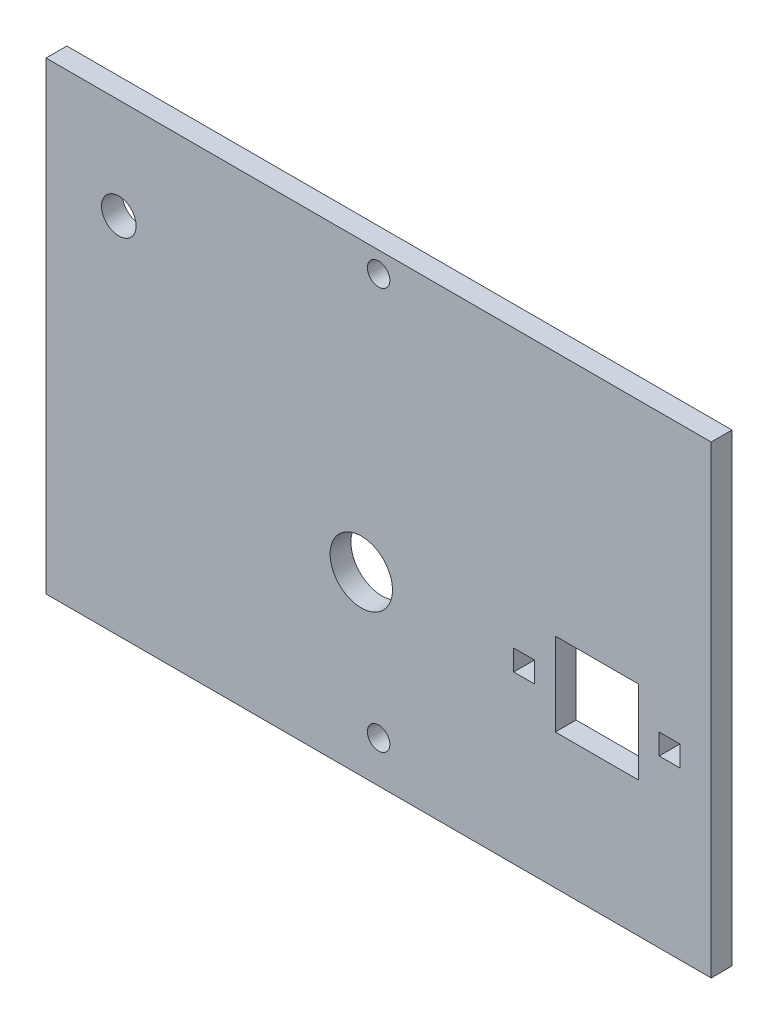
SolidWorks part; units mm, degrees
ref_plane "Alzado" through (0, 0, 0) normal (0, 0, 1) x (1, 0, 0)
ref_plane "Planta" through (0, 0, 0) normal (0, 1, 0) x (1, 0, 0)
ref_plane "Vista lateral" through (0, 0, 0) normal (1, 0, 0) x (0, 0, -1)
sketch "Croquis1" plane through (0, 0, 0) normal (0, 0, 1) x (1, 0, 0)
  line L1 (-48, -33.5) -> (48, -33.5)
  line L2 (-48, -33.5) -> (-48, 33.5)
  line L3 (-48, 33.5) -> (48, 33.5)
  line L4 (48, -33.5) -> (48, 33.5)
  line L5 (-48, -33.5) -> (48, 33.5) construction
  line L6 (-48, 33.5) -> (48, -33.5) construction
  point P0 (0, 0)
  dimension "D1" = 96
  dimension "D2" = 67
extrude "Saliente-Extruir1" add sketch "Croquis1" along normal blind 3
sketch "Croquis2" plane through (0, 0, 0) normal (0, 0, 1) x (1, 0, 0)
  line L0 (48, 33.5) -> (-48, 33.5) construction
  line L1 (-48, 33.5) -> (-48, -33.5) construction
  line L2 (-48, -33.5) -> (48, -33.5) construction
  line L3 (48, -33.5) -> (48, 33.5) construction
  line L4 (25.5, -2) -> (37.5, -2)
  line L5 (25.5, -2) -> (25.5, -14)
  line L6 (25.5, -14) -> (37.5, -14)
  line L7 (37.5, -2) -> (37.5, -14)
  line L8 (25.5, -2) -> (37.5, -14) construction
  line L9 (25.5, -14) -> (37.5, -2) construction
  line L11 (19.5, -9.5) -> (22.5, -9.5)
  line L12 (19.5, -9.5) -> (19.5, -6.5)
  line L13 (19.5, -6.5) -> (22.5, -6.5)
  line L14 (22.5, -9.5) -> (22.5, -6.5)
  line L15 (19.5, -9.5) -> (22.5, -6.5) construction
  line L16 (19.5, -6.5) -> (22.5, -9.5) construction
  line L17 (40.5, -9.5) -> (43.5, -9.5)
  line L18 (40.5, -9.5) -> (40.5, -6.5)
  line L19 (40.5, -6.5) -> (43.5, -6.5)
  line L20 (43.5, -9.5) -> (43.5, -6.5)
  line L21 (40.5, -9.5) -> (43.5, -6.5) construction
  line L22 (40.5, -6.5) -> (43.5, -9.5) construction
  circle A0 centre (-37.5, 19) radius 2.5
  circle A1 centre (-2.5, -8) radius 4.5
  circle A2 centre (0, 30.5) radius 1.625 construction
  circle A3 centre (0, -27.5) radius 1.625 construction
  circle A4 centre (0, 30.5) radius 1.625
  circle A5 centre (0, -27.5) radius 1.625
  point P10 (31.5, -8)
  point P23 (21, -8)
  point P28 (42, -8)
  point P33 (0, 0)
  point P34 (0, 0)
  point P35 (16.7224, -11.2353)
  point P36 (0, 0)
  point P37 (15.4432, -6.5)
  dimension "D1" = 5
  dimension "D2" = 14.5
  dimension "D3" = 10.5
  dimension "D4" = 9
  dimension "D5" = 25.5
  dimension "D6" = 45.5
  dimension "D7" = 12
  dimension "D8" = 10.5
  dimension "D9" = 3
  dimension "D10" = 3
  dimension "D11" = 3
extrude "Cortar-Extruir1" cut sketch "Croquis2" along normal through all
sketch "Sketch3" plane through (0, 0, 3) normal (0, 0, 1) x (1, 0, 0)
  line L0 (-5.5534, 7.4138) -> (-7.3809, 8.9287)
  line L1 (-7.3809, 8.9287) -> (-8.4496, 8.9293)
  line L2 (-8.4594, 13.0301) -> (-7.3709, 13.0385)
  line L3 (-7.3709, 13.0385) -> (-5.4893, 14.597)
  line L4 (-12.2452, -0.2207) -> (-11.9045, 0.2103)
  line L5 (-11.9045, 0.2103) -> (-10.5652, -1.129)
  line L6 (-10.5652, -1.129) -> (-9.226, -2.4682)
  line L7 (-9.226, -2.4682) -> (-9.5723, -2.9498)
  line L8 (-11.1649, -7.1254) -> (-11.1929, -7.3082)
  line L9 (-11.1929, -7.3082) -> (-13.0965, -7.3082)
  line L10 (-13.0965, -7.3082) -> (-15, -7.3082)
  line L11 (-15, -7.3082) -> (-14.9678, -6.9791)
  line L12 (-9.5247, -0.0724) -> (-10.8537, 1.2572)
  line L13 (-10.8537, 1.2572) -> (-10.6676, 1.4249)
  line L14 (-3.5202, 4.4696) -> (-3.2398, 4.5)
  line L15 (-3.2398, 4.5) -> (-3.2398, 2.5703)
  line L16 (-3.2398, 2.5703) -> (-3.2398, 0.6405)
  line L17 (-3.2398, 0.6405) -> (-3.3982, 0.6404)
  line L18 (-12.2452, -0.2207) -> (-11.9045, 0.2103)
  line L19 (-11.9045, 0.2103) -> (-10.5652, -1.129)
  line L20 (-10.5652, -1.129) -> (-9.226, -2.4682)
  line L21 (-9.226, -2.4682) -> (-9.5723, -2.9498)
  line L22 (-11.1649, -7.1254) -> (-11.1929, -7.3082)
  line L23 (-11.1929, -7.3082) -> (-13.0965, -7.3082)
  line L24 (-13.0965, -7.3082) -> (-15, -7.3082)
  line L25 (-15, -7.3082) -> (-14.9678, -6.9791)
  line L26 (-9.5247, -0.0724) -> (-10.8537, 1.2572)
  line L27 (-10.8537, 1.2572) -> (-10.6676, 1.4249)
  line L28 (-3.5202, 4.4696) -> (-3.2398, 4.5)
  line L29 (-3.2398, 4.5) -> (-3.2398, 2.5703)
  line L30 (-3.2398, 2.5703) -> (-3.2398, 0.6405)
  line L31 (-3.2398, 0.6405) -> (-3.3982, 0.6404)
  line L32 (7.2452, -0.2246) -> (6.9045, 0.2064)
  line L33 (6.9045, 0.2064) -> (5.5653, -1.1328)
  line L34 (5.5653, -1.1328) -> (4.226, -2.4721)
  line L35 (4.226, -2.4721) -> (4.5723, -2.9536)
  line L36 (6.1649, -7.1292) -> (6.1929, -7.3121)
  line L37 (6.1929, -7.3121) -> (8.0965, -7.3121)
  line L38 (8.0965, -7.3121) -> (10, -7.3121)
  line L39 (10, -7.3121) -> (9.9678, -6.9829)
  line L40 (4.5247, -0.0763) -> (5.8537, 1.2534)
  line L41 (5.8537, 1.2534) -> (5.6676, 1.421)
  line L42 (-1.4798, 4.4657) -> (-1.7602, 4.4962)
  line L43 (-1.7602, 4.4962) -> (-1.7602, 2.5664)
  line L44 (-1.7602, 2.5664) -> (-1.7602, 0.6367)
  line L45 (-1.7602, 0.6367) -> (-1.6017, 0.6366)
  spline S6 degree 3 poles (2.1798, 5.1128) (2.0212, 5.1868) (1.8251, 5.3837) (1.7541, 5.5401) knots 0 0 0 0 1 1 1 1
  spline S7 degree 3 poles (1.7541, 5.5401) (1.6866, 5.6887) (1.6805, 5.9358) (1.7407, 6.0799) knots 0 0 0 0 1 1 1 1
  spline S8 degree 3 poles (1.7407, 6.0799) (1.7647, 6.1374) (1.8882, 6.3198) (2.0151, 6.4853) knots 0 0 0 0 1 1 1 1
  spline S9 degree 3 poles (2.0151, 6.4853) (2.8091, 7.5204) (3.2972, 8.6684) (3.4875, 9.9482) knots 0 0 0 0 1 1 1 1
  spline S10 degree 3 poles (3.4875, 9.9482) (3.5521, 10.3829) (3.5739, 11.2404) (3.5311, 11.6623) knots 0 0 0 0 1 1 1 1
  spline S11 degree 3 poles (3.5311, 11.6623) (3.3809, 13.1412) (2.8186, 14.5037) (1.8919, 15.6347) knots 0 0 0 0 1 1 1 1
  spline S12 degree 3 poles (1.8919, 15.6347) (1.5927, 15.9997) (1.5659, 16.0534) (1.5661, 16.2873) knots 0 0 0 0 1 1 1 1
  spline S13 degree 3 poles (1.5661, 16.2873) (1.5662, 16.5274) (1.6362, 16.6705) (1.8456, 16.8588) knots 0 0 0 0 1 1 1 1
  spline S14 degree 3 poles (1.8456, 16.8588) (2.085, 17.074) (2.3614, 17.1164) (2.6354, 16.9798) knots 0 0 0 0 1 1 1 1
  spline S15 degree 3 poles (2.6354, 16.9798) (2.7982, 16.8988) (3.059, 16.6076) (3.4139, 16.1109) knots 0 0 0 0 1 1 1 1
  spline S16 degree 3 poles (3.4139, 16.1109) (5.55, 13.1214) (5.6127, 9.1441) (3.572, 6.0768) knots 0 0 0 0 1 1 1 1
  spline S17 degree 3 poles (3.572, 6.0768) (3.2805, 5.6386) (2.98, 5.2704) (2.8261, 5.1626) knots 0 0 0 0 1 1 1 1
  spline S18 degree 3 poles (2.8261, 5.1626) (2.6598, 5.0462) (2.3702, 5.0239) (2.1798, 5.1128) knots 0 0 0 0 1 1 1 1
  spline S19 degree 3 poles (-3.3936, 5.6887) (-3.5414, 5.7438) (-3.4712, 5.6877) (-5.5534, 7.4138) knots 0 0 0 0 1 1 1 1
  spline S20 degree 3 poles (-8.4496, 8.9293) (-9.4614, 8.9299) (-9.5254, 8.9332) (-9.6513, 8.9902) knots 0 0 0 0 1 1 1 1
  spline S21 degree 3 poles (-9.6513, 8.9902) (-9.8168, 9.0652) (-9.9049, 9.1462) (-9.9867, 9.298) knots 0 0 0 0 1 1 1 1
  spline S22 degree 3 poles (-9.9867, 9.298) (-10.0491, 9.414) (-10.0504, 9.4452) (-10.0587, 10.9165) knots 0 0 0 0 1 1 1 1
  spline S23 degree 3 poles (-10.0587, 10.9165) (-10.0641, 11.8817) (-10.0562, 12.4571) (-10.0366, 12.5299) knots 0 0 0 0 1 1 1 1
  spline S24 degree 3 poles (-10.0366, 12.5299) (-9.9899, 12.7034) (-9.8513, 12.8723) (-9.6909, 12.9513) knots 0 0 0 0 1 1 1 1
  spline S25 degree 3 poles (-9.6909, 12.9513) (-9.5492, 13.0211) (-9.5382, 13.0218) (-8.4594, 13.0301) knots 0 0 0 0 1 1 1 1
  spline S26 degree 3 poles (-5.4893, 14.597) (-4.4545, 15.4541) (-3.5691, 16.1801) (-3.5218, 16.2103) knots 0 0 0 0 1 1 1 1
  spline S27 degree 3 poles (-3.5218, 16.2103) (-3.4108, 16.2812) (-3.106, 16.3067) (-2.957, 16.2575) knots 0 0 0 0 1 1 1 1
  spline S28 degree 3 poles (-2.957, 16.2575) (-2.895, 16.237) (-2.7875, 16.1679) (-2.7179, 16.1037) knots 0 0 0 0 1 1 1 1
  spline S29 degree 3 poles (-2.7179, 16.1037) (-2.4811, 15.8855) (-2.4979, 16.2961) (-2.5066, 10.9221) knots 0 0 0 0 1 1 1 1
  spline S30 degree 3 poles (-2.5066, 10.9221) (-2.5138, 6.4591) (-2.5177, 6.1296) (-2.5652, 6.043) knots 0 0 0 0 1 1 1 1
  spline S31 degree 3 poles (-2.5652, 6.043) (-2.729, 5.7436) (-3.1068, 5.582) (-3.3936, 5.6887) knots 0 0 0 0 1 1 1 1
  spline S32 degree 3 poles (-0.1844, 7.4786) (-0.3419, 7.5501) (-0.5386, 7.7468) (-0.6101, 7.9043) knots 0 0 0 0 1 1 1 1
  spline S33 degree 3 poles (-0.6101, 7.9043) (-0.6448, 7.9807) (-0.6662, 8.0951) (-0.6666, 8.2063) knots 0 0 0 0 1 1 1 1
  spline S34 degree 3 poles (-0.6666, 8.2063) (-0.6672, 8.3614) (-0.6528, 8.409) (-0.5591, 8.561) knots 0 0 0 0 1 1 1 1
  spline S35 degree 3 poles (-0.5591, 8.561) (-0.2284, 9.0979) (-0.1539, 9.2359) (-0.0493, 9.5049) knots 0 0 0 0 1 1 1 1
  spline S36 degree 3 poles (-0.0493, 9.5049) (0.4608, 10.8161) (0.2776, 12.2295) (-0.5491, 13.3616) knots 0 0 0 0 1 1 1 1
  spline S37 degree 3 poles (-0.5491, 13.3616) (-0.805, 13.712) (-0.8478, 13.8544) (-0.7737, 14.1093) knots 0 0 0 0 1 1 1 1
  spline S38 degree 3 poles (-0.7737, 14.1093) (-0.7168, 14.3051) (-0.5172, 14.5405) (-0.3322, 14.63) knots 0 0 0 0 1 1 1 1
  spline S39 degree 3 poles (-0.3322, 14.63) (-0.1533, 14.7166) (0.109, 14.7135) (0.2812, 14.6228) knots 0 0 0 0 1 1 1 1
  spline S40 degree 3 poles (0.2812, 14.6228) (0.6098, 14.4497) (1.2089, 13.478) (1.4602, 12.7104) knots 0 0 0 0 1 1 1 1
  spline S41 degree 3 poles (1.4602, 12.7104) (1.667, 12.0788) (1.7404, 11.5342) (1.7178, 10.7982) knots 0 0 0 0 1 1 1 1
  spline S42 degree 3 poles (1.7178, 10.7982) (1.6991, 10.1874) (1.6285, 9.7645) (1.4592, 9.2489) knots 0 0 0 0 1 1 1 1
  spline S43 degree 3 poles (1.4592, 9.2489) (1.2753, 8.6889) (0.7747, 7.7823) (0.5405, 7.5853) knots 0 0 0 0 1 1 1 1
  spline S44 degree 3 poles (0.5405, 7.5853) (0.3389, 7.4156) (0.0484, 7.3729) (-0.1844, 7.4786) knots 0 0 0 0 1 1 1 1
  spline S45 degree 3 poles (-11.0666, -17.1668) (-11.3305, -17.0059) (-12.2194, -15.988) (-12.7344, -15.257) knots 0 0 0 0 1 1 1 1
  spline S46 degree 3 poles (-12.7344, -15.257) (-13.9173, -13.5781) (-14.6586, -11.64) (-14.9174, -9.5495) knots 0 0 0 0 1 1 1 1
  spline S47 degree 3 poles (-14.9174, -9.5495) (-14.9586, -9.2169) (-14.9922, -8.9057) (-14.9922, -8.858) knots 0 0 0 0 1 1 1 1
  spline S48 degree 3 poles (-14.9922, -8.858) (-14.9922, -8.7763) (-14.8815, -8.7712) (-13.0956, -8.7712) knots 0 0 0 0 1 1 1 1
  spline S49 degree 3 poles (-13.0956, -8.7712) (-11.0132, -8.7712) (-11.1398, -8.7522) (-11.1398, -9.0653) knots 0 0 0 0 1 1 1 1
  spline S50 degree 3 poles (-11.1398, -9.0653) (-11.1398, -9.3231) (-10.9404, -10.2417) (-10.7709, -10.7647) knots 0 0 0 0 1 1 1 1
  spline S51 degree 3 poles (-10.7709, -10.7647) (-10.5495, -11.448) (-10.002, -12.5356) (-9.5918, -13.107) knots 0 0 0 0 1 1 1 1
  spline S52 degree 3 poles (-9.5918, -13.107) (-9.4106, -13.3595) (-9.0278, -13.8126) (-8.7412, -14.1139) knots 0 0 0 0 1 1 1 1
  spline S53 degree 3 poles (-8.7412, -14.1139) (-7.8936, -15.0051) (-7.8967, -15.0171) (-9.29, -16.2364) knots 0 0 0 0 1 1 1 1
  spline S54 degree 3 poles (-9.29, -16.2364) (-9.8536, -16.7296) (-10.3633, -17.1601) (-10.4225, -17.1931) knots 0 0 0 0 1 1 1 1
  spline S55 degree 3 poles (-10.4225, -17.1931) (-10.5816, -17.2815) (-10.8998, -17.2685) (-11.0666, -17.1668) knots 0 0 0 0 1 1 1 1
  spline S56 degree 3 poles (-14.9678, -6.9791) (-14.7179, -4.4276) (-13.8315, -2.2274) (-12.2452, -0.2207) knots 0 0 0 0 1 1 1 1
  spline S57 degree 3 poles (-9.5723, -2.9498) (-9.7627, -3.2147) (-10.0597, -3.7057) (-10.2322, -4.041) knots 0 0 0 0 1 1 1 1
  spline S58 degree 3 poles (-10.2322, -4.041) (-10.7181, -4.9853) (-10.959, -5.7821) (-11.1649, -7.1254) knots 0 0 0 0 1 1 1 1
  spline S59 degree 3 poles (-10.6676, 1.4249) (-10.017, 2.0107) (-8.9985, 2.6992) (-8.1212, 3.1462) knots 0 0 0 0 1 1 1 1
  spline S60 degree 3 poles (-8.1212, 3.1462) (-6.662, 3.8898) (-5.3294, 4.2731) (-3.5202, 4.4696) knots 0 0 0 0 1 1 1 1
  spline S61 degree 3 poles (-3.3982, 0.6404) (-3.6091, 0.6404) (-4.2428, 0.5269) (-4.7349, 0.4011) knots 0 0 0 0 1 1 1 1
  spline S62 degree 3 poles (-4.7349, 0.4011) (-5.7843, 0.1328) (-7.0878, -0.5165) (-7.8725, -1.1618) knots 0 0 0 0 1 1 1 1
  spline S63 degree 3 poles (-7.8725, -1.1618) (-7.9932, -1.2611) (-8.1152, -1.3558) (-8.1438, -1.3722) knots 0 0 0 0 1 1 1 1
  spline S64 degree 3 poles (-8.1438, -1.3722) (-8.1723, -1.3887) (-8.7937, -0.8038) (-9.5246, -0.0724) knots 0 0 0 0 1 1 1 1
  spline S65 degree 3 poles (-11.0666, -17.1668) (-11.3305, -17.0059) (-12.2194, -15.988) (-12.7344, -15.257) knots 0 0 0 0 1 1 1 1
  spline S66 degree 3 poles (-12.7344, -15.257) (-13.9173, -13.5781) (-14.6586, -11.64) (-14.9174, -9.5495) knots 0 0 0 0 1 1 1 1
  spline S67 degree 3 poles (-14.9174, -9.5495) (-14.9586, -9.2169) (-14.9922, -8.9057) (-14.9922, -8.858) knots 0 0 0 0 1 1 1 1
  spline S68 degree 3 poles (-14.9922, -8.858) (-14.9922, -8.7763) (-14.8815, -8.7712) (-13.0956, -8.7712) knots 0 0 0 0 1 1 1 1
  spline S69 degree 3 poles (-13.0956, -8.7712) (-11.0132, -8.7712) (-11.1398, -8.7522) (-11.1398, -9.0653) knots 0 0 0 0 1 1 1 1
  spline S70 degree 3 poles (-11.1398, -9.0653) (-11.1398, -9.3231) (-10.9404, -10.2417) (-10.7709, -10.7647) knots 0 0 0 0 1 1 1 1
  spline S71 degree 3 poles (-10.7709, -10.7647) (-10.5495, -11.448) (-10.002, -12.5356) (-9.5918, -13.107) knots 0 0 0 0 1 1 1 1
  spline S72 degree 3 poles (-9.5918, -13.107) (-9.4106, -13.3595) (-9.0278, -13.8126) (-8.7412, -14.1139) knots 0 0 0 0 1 1 1 1
  spline S73 degree 3 poles (-8.7412, -14.1139) (-7.8936, -15.0051) (-7.8967, -15.0171) (-9.29, -16.2364) knots 0 0 0 0 1 1 1 1
  spline S74 degree 3 poles (-9.29, -16.2364) (-9.8536, -16.7296) (-10.3633, -17.1601) (-10.4225, -17.1931) knots 0 0 0 0 1 1 1 1
  spline S75 degree 3 poles (-10.4225, -17.1931) (-10.5816, -17.2815) (-10.8998, -17.2685) (-11.0666, -17.1668) knots 0 0 0 0 1 1 1 1
  spline S76 degree 3 poles (-14.9678, -6.9791) (-14.7179, -4.4276) (-13.8315, -2.2274) (-12.2452, -0.2207) knots 0 0 0 0 1 1 1 1
  spline S77 degree 3 poles (-9.5723, -2.9498) (-9.7627, -3.2147) (-10.0597, -3.7057) (-10.2322, -4.041) knots 0 0 0 0 1 1 1 1
  spline S78 degree 3 poles (-10.2322, -4.041) (-10.7181, -4.9853) (-10.959, -5.7821) (-11.1649, -7.1254) knots 0 0 0 0 1 1 1 1
  spline S79 degree 3 poles (-10.6676, 1.4249) (-10.017, 2.0107) (-8.9985, 2.6992) (-8.1212, 3.1462) knots 0 0 0 0 1 1 1 1
  spline S80 degree 3 poles (-8.1212, 3.1462) (-6.662, 3.8898) (-5.3294, 4.2731) (-3.5202, 4.4696) knots 0 0 0 0 1 1 1 1
  spline S81 degree 3 poles (-3.3982, 0.6404) (-3.6091, 0.6404) (-4.2428, 0.5269) (-4.7349, 0.4011) knots 0 0 0 0 1 1 1 1
  spline S82 degree 3 poles (-4.7349, 0.4011) (-5.7843, 0.1328) (-7.0878, -0.5165) (-7.8725, -1.1618) knots 0 0 0 0 1 1 1 1
  spline S83 degree 3 poles (-7.8725, -1.1618) (-7.9932, -1.2611) (-8.1152, -1.3558) (-8.1438, -1.3722) knots 0 0 0 0 1 1 1 1
  spline S84 degree 3 poles (-8.1438, -1.3722) (-8.1723, -1.3887) (-8.7937, -0.8038) (-9.5246, -0.0724) knots 0 0 0 0 1 1 1 1
  spline S85 degree 3 poles (6.0667, -17.1706) (6.3305, -17.0097) (7.2194, -15.9918) (7.7344, -15.2609) knots 0 0 0 0 1 1 1 1
  spline S86 degree 3 poles (7.7344, -15.2609) (8.9174, -13.5819) (9.6586, -11.6439) (9.9174, -9.5533) knots 0 0 0 0 1 1 1 1
  spline S87 degree 3 poles (9.9174, -9.5533) (9.9585, -9.2207) (9.9923, -8.9096) (9.9923, -8.8618) knots 0 0 0 0 1 1 1 1
  spline S88 degree 3 poles (9.9923, -8.8618) (9.9923, -8.7801) (9.8815, -8.775) (8.0957, -8.775) knots 0 0 0 0 1 1 1 1
  spline S89 degree 3 poles (8.0957, -8.775) (6.0133, -8.775) (6.1398, -8.756) (6.1398, -9.0692) knots 0 0 0 0 1 1 1 1
  spline S90 degree 3 poles (6.1398, -9.0692) (6.1398, -9.3269) (5.9404, -10.2455) (5.771, -10.7685) knots 0 0 0 0 1 1 1 1
  spline S91 degree 3 poles (5.771, -10.7685) (5.5496, -11.4519) (5.0021, -12.5395) (4.5918, -13.1109) knots 0 0 0 0 1 1 1 1
  spline S92 degree 3 poles (4.5918, -13.1109) (4.4106, -13.3633) (4.0279, -13.8164) (3.7413, -14.1178) knots 0 0 0 0 1 1 1 1
  spline S93 degree 3 poles (3.7413, -14.1178) (2.8937, -15.009) (2.8968, -15.0209) (4.2901, -16.2402) knots 0 0 0 0 1 1 1 1
  spline S94 degree 3 poles (4.2901, -16.2402) (4.8537, -16.7335) (5.3633, -17.164) (5.4225, -17.1969) knots 0 0 0 0 1 1 1 1
  spline S95 degree 3 poles (5.4225, -17.1969) (5.5817, -17.2854) (5.8998, -17.2724) (6.0667, -17.1706) knots 0 0 0 0 1 1 1 1
  spline S96 degree 3 poles (9.9678, -6.9829) (9.7179, -4.4315) (8.8316, -2.2313) (7.2452, -0.2246) knots 0 0 0 0 1 1 1 1
  spline S97 degree 3 poles (4.5723, -2.9536) (4.7628, -3.2185) (5.0597, -3.7095) (5.2322, -4.0448) knots 0 0 0 0 1 1 1 1
  spline S98 degree 3 poles (5.2322, -4.0448) (5.7181, -4.9891) (5.959, -5.786) (6.1649, -7.1292) knots 0 0 0 0 1 1 1 1
  spline S99 degree 3 poles (5.6676, 1.421) (5.017, 2.0069) (3.9986, 2.6954) (3.1213, 3.1424) knots 0 0 0 0 1 1 1 1
  spline S100 degree 3 poles (3.1213, 3.1424) (1.662, 3.886) (0.3295, 4.2692) (-1.4798, 4.4657) knots 0 0 0 0 1 1 1 1
  spline S101 degree 3 poles (-1.6017, 0.6366) (-1.3908, 0.6365) (-0.7571, 0.523) (-0.2651, 0.3972) knots 0 0 0 0 1 1 1 1
  spline S102 degree 3 poles (-0.2651, 0.3972) (0.7844, 0.1289) (2.0878, -0.5204) (2.8725, -1.1657) knots 0 0 0 0 1 1 1 1
  spline S103 degree 3 poles (2.8725, -1.1657) (2.9932, -1.2649) (3.1153, -1.3596) (3.1438, -1.376) knots 0 0 0 0 1 1 1 1
  spline S104 degree 3 poles (3.1438, -1.376) (3.1723, -1.3925) (3.7937, -0.8076) (4.5247, -0.0763) knots 0 0 0 0 1 1 1 1
sketch "Sketch4" plane through (0, 0, 3) normal (0, 0, 1) x (1, 0, 0)
  circle A0 centre (-37.5, 19) radius 2.5 construction
  spline S8 degree 3 poles (-37.6749, 14.0491) (-37.7146, 14.0761) (-37.7676, 14.126) (-37.7928, 14.1599) knots 0 0 0 0 1 1 1 1
  spline S9 degree 3 poles (-37.7928, 14.1599) (-37.8364, 14.2188) (-37.8384, 14.2472) (-37.8384, 14.8079) knots 0 0 0 0 1 1 1 1
  spline S10 degree 3 poles (-37.8384, 14.8079) (-37.8384, 15.3686) (-37.8364, 15.3969) (-37.7928, 15.4558) knots 0 0 0 0 1 1 1 1
  spline S11 degree 3 poles (-37.7928, 15.4558) (-37.7676, 15.4897) (-37.7146, 15.5396) (-37.6749, 15.5666) knots 0 0 0 0 1 1 1 1
  spline S12 degree 3 poles (-37.6749, 15.5666) (-37.6253, 15.6003) (-37.5706, 15.6157) (-37.5, 15.6157) knots 0 0 0 0 1 1 1 1
  spline S13 degree 3 poles (-37.5, 15.6157) (-37.4294, 15.6157) (-37.3747, 15.6003) (-37.3251, 15.5666) knots 0 0 0 0 1 1 1 1
  spline S14 degree 3 poles (-37.3251, 15.5666) (-37.2854, 15.5396) (-37.2324, 15.4897) (-37.2072, 15.4558) knots 0 0 0 0 1 1 1 1
  spline S15 degree 3 poles (-37.2072, 15.4558) (-37.1636, 15.3969) (-37.1616, 15.3686) (-37.1616, 14.8079) knots 0 0 0 0 1 1 1 1
  spline S16 degree 3 poles (-37.1616, 14.8079) (-37.1616, 14.2471) (-37.1636, 14.2188) (-37.2072, 14.1599) knots 0 0 0 0 1 1 1 1
  spline S17 degree 3 poles (-37.2072, 14.1599) (-37.2324, 14.126) (-37.2854, 14.0761) (-37.3251, 14.0491) knots 0 0 0 0 1 1 1 1
  spline S18 degree 3 poles (-37.3251, 14.0491) (-37.3747, 14.0154) (-37.4294, 14) (-37.5, 14) knots 0 0 0 0 1 1 1 1
  spline S19 degree 3 poles (-37.5, 14) (-37.5706, 14) (-37.6253, 14.0154) (-37.6749, 14.0491) knots 0 0 0 0 1 1 1 1
  spline S20 degree 3 poles (-40.9439, 15.3966) (-40.9972, 15.4208) (-41.0548, 15.469) (-41.0803, 15.5107) knots 0 0 0 0 1 1 1 1
  spline S21 degree 3 poles (-41.0803, 15.5107) (-41.1045, 15.5505) (-41.1304, 15.6153) (-41.1379, 15.6549) knots 0 0 0 0 1 1 1 1
  spline S22 degree 3 poles (-41.1379, 15.6549) (-41.1463, 15.6995) (-41.1381, 15.762) (-41.1161, 15.8195) knots 0 0 0 0 1 1 1 1
  spline S23 degree 3 poles (-41.1161, 15.8195) (-41.0897, 15.8885) (-40.982, 16.0102) (-40.6932, 16.2971) knots 0 0 0 0 1 1 1 1
  spline S24 degree 3 poles (-40.6932, 16.2971) (-40.3677, 16.6204) (-40.2926, 16.6844) (-40.2238, 16.6971) knots 0 0 0 0 1 1 1 1
  spline S25 degree 3 poles (-40.2238, 16.6971) (-40.1788, 16.7054) (-40.1056, 16.7054) (-40.0611, 16.6971) knots 0 0 0 0 1 1 1 1
  spline S26 degree 3 poles (-40.0611, 16.6971) (-40.0104, 16.6876) (-39.9501, 16.6517) (-39.8992, 16.6008) knots 0 0 0 0 1 1 1 1
  spline S27 degree 3 poles (-39.8992, 16.6008) (-39.8482, 16.5499) (-39.8124, 16.4896) (-39.8029, 16.4389) knots 0 0 0 0 1 1 1 1
  spline S28 degree 3 poles (-39.8029, 16.4389) (-39.7946, 16.3944) (-39.7946, 16.3212) (-39.8029, 16.2762) knots 0 0 0 0 1 1 1 1
  spline S29 degree 3 poles (-39.8029, 16.2762) (-39.8155, 16.2077) (-39.8792, 16.1324) (-40.1929, 15.8152) knots 0 0 0 0 1 1 1 1
  spline S30 degree 3 poles (-40.1929, 15.8152) (-40.4232, 15.5821) (-40.6013, 15.4204) (-40.655, 15.3954) knots 0 0 0 0 1 1 1 1
  spline S31 degree 3 poles (-40.655, 15.3954) (-40.7031, 15.373) (-40.7669, 15.3547) (-40.7969, 15.3547) knots 0 0 0 0 1 1 1 1
  spline S32 degree 3 poles (-40.7969, 15.3547) (-40.827, 15.3547) (-40.8931, 15.3735) (-40.9439, 15.3966) knots 0 0 0 0 1 1 1 1
  spline S33 degree 3 poles (-34.345, 15.3954) (-34.3986, 15.4204) (-34.577, 15.5823) (-34.8073, 15.8152) knots 0 0 0 0 1 1 1 1
  spline S34 degree 3 poles (-34.8073, 15.8152) (-35.0439, 16.0544) (-35.1879, 16.217) (-35.1975, 16.2557) knots 0 0 0 0 1 1 1 1
  spline S35 degree 3 poles (-35.1975, 16.2557) (-35.2059, 16.2894) (-35.208, 16.3598) (-35.2021, 16.412) knots 0 0 0 0 1 1 1 1
  spline S36 degree 3 poles (-35.2021, 16.412) (-35.1962, 16.4642) (-35.1707, 16.5361) (-35.1453, 16.5718) knots 0 0 0 0 1 1 1 1
  spline S37 degree 3 poles (-35.1453, 16.5718) (-35.1199, 16.6074) (-35.0655, 16.6525) (-35.0245, 16.672) knots 0 0 0 0 1 1 1 1
  spline S38 degree 3 poles (-35.0245, 16.672) (-34.9834, 16.6915) (-34.909, 16.7075) (-34.8592, 16.7075) knots 0 0 0 0 1 1 1 1
  spline S39 degree 3 poles (-34.8592, 16.7075) (-34.8094, 16.7075) (-34.7421, 16.6935) (-34.7097, 16.6764) knots 0 0 0 0 1 1 1 1
  spline S40 degree 3 poles (-34.7097, 16.6764) (-34.6772, 16.6593) (-34.4824, 16.4751) (-34.2768, 16.267) knots 0 0 0 0 1 1 1 1
  spline S41 degree 3 poles (-34.2768, 16.267) (-34.0046, 15.9916) (-33.8958, 15.8664) (-33.8766, 15.8067) knots 0 0 0 0 1 1 1 1
  spline S42 degree 3 poles (-33.8766, 15.8067) (-33.8619, 15.7608) (-33.8569, 15.6936) (-33.8653, 15.6539) knots 0 0 0 0 1 1 1 1
  spline S43 degree 3 poles (-33.8653, 15.6539) (-33.8735, 15.6149) (-33.8993, 15.5518) (-33.9224, 15.5136) knots 0 0 0 0 1 1 1 1
  spline S44 degree 3 poles (-33.9224, 15.5136) (-33.9456, 15.4754) (-34.0066, 15.4238) (-34.058, 15.399) knots 0 0 0 0 1 1 1 1
  spline S45 degree 3 poles (-34.058, 15.399) (-34.1093, 15.3741) (-34.1753, 15.354) (-34.2045, 15.3542) knots 0 0 0 0 1 1 1 1
  spline S46 degree 3 poles (-34.2045, 15.3542) (-34.2338, 15.3545) (-34.297, 15.373) (-34.345, 15.3954) knots 0 0 0 0 1 1 1 1
  spline S47 degree 3 poles (-42.2816, 18.6747) (-42.3117, 18.6869) (-42.3593, 18.7185) (-42.3874, 18.7448) knots 0 0 0 0 1 1 1 1
  spline S48 degree 3 poles (-42.3874, 18.7448) (-42.4156, 18.7711) (-42.4525, 18.8191) (-42.4693, 18.8516) knots 0 0 0 0 1 1 1 1
  spline S49 degree 3 poles (-42.4693, 18.8516) (-42.4862, 18.884) (-42.5, 18.9538) (-42.5, 19.0066) knots 0 0 0 0 1 1 1 1
  spline S50 degree 3 poles (-42.5, 19.0066) (-42.5, 19.0704) (-42.4835, 19.1271) (-42.4509, 19.1749) knots 0 0 0 0 1 1 1 1
  spline S51 degree 3 poles (-42.4509, 19.1749) (-42.4239, 19.2146) (-42.374, 19.2677) (-42.3401, 19.2928) knots 0 0 0 0 1 1 1 1
  spline S52 degree 3 poles (-42.3401, 19.2928) (-42.2812, 19.3365) (-42.2529, 19.3385) (-41.6921, 19.3385) knots 0 0 0 0 1 1 1 1
  spline S53 degree 3 poles (-41.6921, 19.3385) (-41.1314, 19.3385) (-41.1031, 19.3365) (-41.0442, 19.2928) knots 0 0 0 0 1 1 1 1
  spline S54 degree 3 poles (-41.0442, 19.2928) (-41.0103, 19.2677) (-40.9604, 19.2146) (-40.9334, 19.1749) knots 0 0 0 0 1 1 1 1
  spline S55 degree 3 poles (-40.9334, 19.1749) (-40.8997, 19.1253) (-40.8843, 19.0706) (-40.8843, 19) knots 0 0 0 0 1 1 1 1
  spline S56 degree 3 poles (-40.8843, 19) (-40.8843, 18.9295) (-40.8996, 18.8747) (-40.9334, 18.8251) knots 0 0 0 0 1 1 1 1
  spline S57 degree 3 poles (-40.9334, 18.8251) (-40.9604, 18.7854) (-41.0102, 18.7324) (-41.0441, 18.7073) knots 0 0 0 0 1 1 1 1
  spline S58 degree 3 poles (-41.0441, 18.7073) (-41.1024, 18.664) (-41.1356, 18.6614) (-41.6664, 18.657) knots 0 0 0 0 1 1 1 1
  spline S59 degree 3 poles (-41.6664, 18.657) (-42.0089, 18.6542) (-42.2483, 18.6611) (-42.2816, 18.6747) knots 0 0 0 0 1 1 1 1
  spline S60 degree 3 poles (-33.8974, 18.6747) (-33.9274, 18.6869) (-33.975, 18.7185) (-34.0032, 18.7448) knots 0 0 0 0 1 1 1 1
  spline S61 degree 3 poles (-34.0032, 18.7448) (-34.0313, 18.7711) (-34.0682, 18.8191) (-34.085, 18.8516) knots 0 0 0 0 1 1 1 1
  spline S62 degree 3 poles (-34.085, 18.8516) (-34.1019, 18.884) (-34.1157, 18.9538) (-34.1157, 19.0066) knots 0 0 0 0 1 1 1 1
  spline S63 degree 3 poles (-34.1157, 19.0066) (-34.1157, 19.0704) (-34.0992, 19.1271) (-34.0666, 19.1749) knots 0 0 0 0 1 1 1 1
  spline S64 degree 3 poles (-34.0666, 19.1749) (-34.0396, 19.2146) (-33.9897, 19.2677) (-33.9558, 19.2928) knots 0 0 0 0 1 1 1 1
  spline S65 degree 3 poles (-33.9558, 19.2928) (-33.8969, 19.3365) (-33.8686, 19.3385) (-33.3079, 19.3385) knots 0 0 0 0 1 1 1 1
  spline S66 degree 3 poles (-33.3079, 19.3385) (-32.7472, 19.3385) (-32.7189, 19.3365) (-32.6599, 19.2928) knots 0 0 0 0 1 1 1 1
  spline S67 degree 3 poles (-32.6599, 19.2928) (-32.626, 19.2677) (-32.5761, 19.2146) (-32.5491, 19.1749) knots 0 0 0 0 1 1 1 1
  spline S68 degree 3 poles (-32.5491, 19.1749) (-32.5154, 19.1253) (-32.5, 19.0706) (-32.5, 19) knots 0 0 0 0 1 1 1 1
  spline S69 degree 3 poles (-32.5, 19) (-32.5, 18.9295) (-32.5154, 18.8747) (-32.5491, 18.8251) knots 0 0 0 0 1 1 1 1
  spline S70 degree 3 poles (-32.5491, 18.8251) (-32.5761, 18.7854) (-32.626, 18.7324) (-32.6598, 18.7073) knots 0 0 0 0 1 1 1 1
  spline S71 degree 3 poles (-32.6598, 18.7073) (-32.7182, 18.664) (-32.7513, 18.6614) (-33.2821, 18.657) knots 0 0 0 0 1 1 1 1
  spline S72 degree 3 poles (-33.2821, 18.657) (-33.6246, 18.6542) (-33.864, 18.6611) (-33.8974, 18.6747) knots 0 0 0 0 1 1 1 1
  spline S73 degree 3 poles (-40.3057, 21.3341) (-40.3417, 21.3568) (-40.5304, 21.5361) (-40.7249, 21.7325) knots 0 0 0 0 1 1 1 1
  spline S74 degree 3 poles (-40.7249, 21.7325) (-40.9195, 21.9289) (-41.089, 22.1172) (-41.1016, 22.151) knots 0 0 0 0 1 1 1 1
  spline S75 degree 3 poles (-41.1016, 22.151) (-41.1141, 22.1848) (-41.1245, 22.2497) (-41.1245, 22.2952) knots 0 0 0 0 1 1 1 1
  spline S76 degree 3 poles (-41.1245, 22.2952) (-41.1245, 22.345) (-41.1047, 22.4071) (-41.0748, 22.4515) knots 0 0 0 0 1 1 1 1
  spline S77 degree 3 poles (-41.0748, 22.4515) (-41.0475, 22.492) (-40.992, 22.5475) (-40.9515, 22.5748) knots 0 0 0 0 1 1 1 1
  spline S78 degree 3 poles (-40.9515, 22.5748) (-40.9063, 22.6053) (-40.8451, 22.6245) (-40.793, 22.6245) knots 0 0 0 0 1 1 1 1
  spline S79 degree 3 poles (-40.793, 22.6245) (-40.7464, 22.6245) (-40.6766, 22.6108) (-40.6379, 22.594) knots 0 0 0 0 1 1 1 1
  spline S80 degree 3 poles (-40.6379, 22.594) (-40.5993, 22.5772) (-40.4036, 22.3979) (-40.203, 22.1955) knots 0 0 0 0 1 1 1 1
  spline S81 degree 3 poles (-40.203, 22.1955) (-40.0025, 21.9931) (-39.8281, 21.7999) (-39.8155, 21.7661) knots 0 0 0 0 1 1 1 1
  spline S82 degree 3 poles (-39.8155, 21.7661) (-39.8029, 21.7323) (-39.7927, 21.6684) (-39.7929, 21.6242) knots 0 0 0 0 1 1 1 1
  spline S83 degree 3 poles (-39.7929, 21.6242) (-39.7931, 21.5799) (-39.8152, 21.5054) (-39.8421, 21.4586) knots 0 0 0 0 1 1 1 1
  spline S84 degree 3 poles (-39.8421, 21.4586) (-39.8689, 21.4119) (-39.9251, 21.3554) (-39.9669, 21.3331) knots 0 0 0 0 1 1 1 1
  spline S85 degree 3 poles (-39.9669, 21.3331) (-40.0088, 21.3108) (-40.0873, 21.2926) (-40.1416, 21.2927) knots 0 0 0 0 1 1 1 1
  spline S86 degree 3 poles (-40.1416, 21.2927) (-40.2006, 21.2927) (-40.2665, 21.3094) (-40.3057, 21.3341) knots 0 0 0 0 1 1 1 1
  spline S87 degree 3 poles (-35.028, 21.3289) (-35.0674, 21.3483) (-35.1196, 21.3922) (-35.144, 21.4264) knots 0 0 0 0 1 1 1 1
  spline S88 degree 3 poles (-35.144, 21.4264) (-35.1683, 21.4607) (-35.1938, 21.5226) (-35.2005, 21.5641) knots 0 0 0 0 1 1 1 1
  spline S89 degree 3 poles (-35.2005, 21.5641) (-35.2072, 21.6056) (-35.2058, 21.6769) (-35.1974, 21.7226) knots 0 0 0 0 1 1 1 1
  spline S90 degree 3 poles (-35.1974, 21.7226) (-35.1844, 21.7927) (-35.1233, 21.8651) (-34.8072, 22.1848) knots 0 0 0 0 1 1 1 1
  spline S91 degree 3 poles (-34.8072, 22.1848) (-34.601, 22.3933) (-34.4007, 22.5775) (-34.3621, 22.5942) knots 0 0 0 0 1 1 1 1
  spline S92 degree 3 poles (-34.3621, 22.5942) (-34.3235, 22.6108) (-34.2537, 22.6245) (-34.207, 22.6245) knots 0 0 0 0 1 1 1 1
  spline S93 degree 3 poles (-34.207, 22.6245) (-34.155, 22.6245) (-34.0938, 22.6053) (-34.0486, 22.5748) knots 0 0 0 0 1 1 1 1
  spline S94 degree 3 poles (-34.0486, 22.5748) (-34.008, 22.5475) (-33.9525, 22.492) (-33.9252, 22.4515) knots 0 0 0 0 1 1 1 1
  spline S95 degree 3 poles (-33.9252, 22.4515) (-33.8953, 22.4071) (-33.8756, 22.345) (-33.8756, 22.2951) knots 0 0 0 0 1 1 1 1
  spline S96 degree 3 poles (-33.8756, 22.2951) (-33.8756, 22.2497) (-33.8859, 22.1848) (-33.8985, 22.151) knots 0 0 0 0 1 1 1 1
  spline S97 degree 3 poles (-33.8985, 22.151) (-33.9111, 22.1172) (-34.0855, 21.9243) (-34.286, 21.7223) knots 0 0 0 0 1 1 1 1
  spline S98 degree 3 poles (-34.286, 21.7223) (-34.4866, 21.5204) (-34.6772, 21.3411) (-34.7097, 21.3239) knots 0 0 0 0 1 1 1 1
  spline S99 degree 3 poles (-34.7097, 21.3239) (-34.7421, 21.3067) (-34.8109, 21.2928) (-34.8625, 21.2931) knots 0 0 0 0 1 1 1 1
  spline S100 degree 3 poles (-34.8625, 21.2931) (-34.9141, 21.2933) (-34.9886, 21.3095) (-35.028, 21.3289) knots 0 0 0 0 1 1 1 1
  spline S101 degree 3 poles (-37.6749, 22.4334) (-37.7146, 22.4604) (-37.7676, 22.5103) (-37.7928, 22.5442) knots 0 0 0 0 1 1 1 1
  spline S102 degree 3 poles (-37.7928, 22.5442) (-37.8364, 22.6031) (-37.8384, 22.6314) (-37.8384, 23.1921) knots 0 0 0 0 1 1 1 1
  spline S103 degree 3 poles (-37.8384, 23.1921) (-37.8384, 23.7529) (-37.8364, 23.7812) (-37.7928, 23.8401) knots 0 0 0 0 1 1 1 1
  spline S104 degree 3 poles (-37.7928, 23.8401) (-37.7676, 23.874) (-37.7146, 23.9239) (-37.6749, 23.9509) knots 0 0 0 0 1 1 1 1
  spline S105 degree 3 poles (-37.6749, 23.9509) (-37.6253, 23.9846) (-37.5706, 24) (-37.5, 24) knots 0 0 0 0 1 1 1 1
  spline S106 degree 3 poles (-37.5, 24) (-37.4294, 24) (-37.3747, 23.9846) (-37.3251, 23.9509) knots 0 0 0 0 1 1 1 1
  spline S107 degree 3 poles (-37.3251, 23.9509) (-37.2854, 23.9239) (-37.2324, 23.874) (-37.2072, 23.8401) knots 0 0 0 0 1 1 1 1
  spline S108 degree 3 poles (-37.2072, 23.8401) (-37.1636, 23.7812) (-37.1616, 23.7528) (-37.1616, 23.1921) knots 0 0 0 0 1 1 1 1
  spline S109 degree 3 poles (-37.1616, 23.1921) (-37.1616, 22.6314) (-37.1636, 22.6031) (-37.2072, 22.5442) knots 0 0 0 0 1 1 1 1
  spline S110 degree 3 poles (-37.2072, 22.5442) (-37.2324, 22.5103) (-37.2854, 22.4604) (-37.3251, 22.4334) knots 0 0 0 0 1 1 1 1
  spline S111 degree 3 poles (-37.3251, 22.4334) (-37.3747, 22.3997) (-37.4294, 22.3843) (-37.5, 22.3843) knots 0 0 0 0 1 1 1 1
  spline S112 degree 3 poles (-37.5, 22.3843) (-37.5706, 22.3843) (-37.6253, 22.3997) (-37.6749, 22.4334) knots 0 0 0 0 1 1 1 1
  point P0 (-37.5, 21.5)
sketch "Sketch5" plane through (0, 0, 3) normal (0, 0, 1) x (1, 0, 0)
  line L0 (33.0588, -1.0832) -> (32.9906, -0.9736)
  line L1 (32.9906, -0.9736) -> (32.9824, 2.0181)
  line L2 (32.9824, 2.0181) -> (32.9742, 5.0098)
  line L3 (32.9742, 5.0098) -> (33.0523, 5.1695)
  line L4 (34.8115, 5.1733) -> (34.8898, 5.0161)
  line L5 (34.8898, 5.0161) -> (34.8898, 2.0536)
  line L6 (35.5645, 2.126) -> (35.5736, 5.0432)
  line L7 (35.5736, 5.0432) -> (35.6394, 5.1661)
  line L8 (37.4962, 1.987) -> (37.488, -0.9128)
  line L9 (37.488, -0.9128) -> (37.4055, -1.0693)
  spline S0 degree 3 poles (26.0182, -1.4529) (25.9405, -1.4255) (25.822, -1.3441) (25.7394, -1.2615) knots 0 0 0 0 1 1 1 1
  spline S1 degree 3 poles (25.7394, -1.2615) (25.4872, -1.0093) (25.5, -1.1862) (25.5, 2.05) knots 0 0 0 0 1 1 1 1
  spline S2 degree 3 poles (25.5, 2.05) (25.5, 5.2426) (25.4908, 5.1029) (25.7161, 5.3473) knots 0 0 0 0 1 1 1 1
  spline S3 degree 3 poles (25.7161, 5.3473) (25.8819, 5.5271) (26.0732, 5.6124) (26.3076, 5.6111) knots 0 0 0 0 1 1 1 1
  spline S4 degree 3 poles (26.3076, 5.6111) (26.41, 5.6105) (26.5408, 5.5903) (26.5984, 5.5663) knots 0 0 0 0 1 1 1 1
  spline S5 degree 3 poles (26.5984, 5.5663) (26.656, 5.5422) (27.8785, 4.8968) (29.3151, 4.1321) knots 0 0 0 0 1 1 1 1
  spline S6 degree 3 poles (29.3151, 4.1321) (31.0321, 3.2181) (31.9663, 2.7042) (32.0415, 2.6323) knots 0 0 0 0 1 1 1 1
  spline S7 degree 3 poles (32.0415, 2.6323) (32.3044, 2.381) (32.3649, 2.0208) (32.1986, 1.6977) knots 0 0 0 0 1 1 1 1
  spline S8 degree 3 poles (32.1986, 1.6977) (32.1495, 1.6022) (32.0615, 1.4861) (32.003, 1.4396) knots 0 0 0 0 1 1 1 1
  spline S9 degree 3 poles (32.003, 1.4396) (31.9046, 1.3614) (27.1767, -1.1737) (26.7012, -1.4032) knots 0 0 0 0 1 1 1 1
  spline S10 degree 3 poles (26.7012, -1.4032) (26.4596, -1.5197) (26.2506, -1.5349) (26.0182, -1.4529) knots 0 0 0 0 1 1 1 1
  spline S11 degree 3 poles (33.4464, -1.4335) (33.2787, -1.3548) (33.1622, -1.2495) (33.0588, -1.0832) knots 0 0 0 0 1 1 1 1
  spline S12 degree 3 poles (33.0523, 5.1695) (33.1408, 5.3504) (33.2627, 5.4653) (33.4616, 5.5554) knots 0 0 0 0 1 1 1 1
  spline S13 degree 3 poles (33.4616, 5.5554) (33.6591, 5.6449) (34.2062, 5.6449) (34.4036, 5.5554) knots 0 0 0 0 1 1 1 1
  spline S14 degree 3 poles (34.4036, 5.5554) (34.601, 5.466) (34.7223, 5.3523) (34.8115, 5.1733) knots 0 0 0 0 1 1 1 1
  spline S15 degree 3 poles (34.8898, 2.0536) (34.8898, -0.8441) (34.8885, -0.9116) (34.8292, -1.034) knots 0 0 0 0 1 1 1 1
  spline S16 degree 3 poles (34.8292, -1.034) (34.7457, -1.2066) (34.599, -1.3495) (34.4188, -1.4337) knots 0 0 0 0 1 1 1 1
  spline S17 degree 3 poles (34.4188, -1.4337) (34.2885, -1.4947) (34.2195, -1.5048) (33.9326, -1.5048) knots 0 0 0 0 1 1 1 1
  spline S18 degree 3 poles (33.9326, -1.5048) (33.6453, -1.5048) (33.577, -1.4948) (33.4464, -1.4335) knots 0 0 0 0 1 1 1 1
  spline S19 degree 3 poles (36.0977, -1.4621) (35.8579, -1.3765) (35.6603, -1.1628) (35.5897, -0.9128) knots 0 0 0 0 1 1 1 1
  spline S20 degree 3 poles (35.5897, -0.9128) (35.565, -0.8253) (35.5579, 0.0247) (35.5645, 2.126) knots 0 0 0 0 1 1 1 1
  spline S21 degree 3 poles (35.6394, 5.1661) (35.7263, 5.3284) (35.9444, 5.5264) (36.0927, 5.5777) knots 0 0 0 0 1 1 1 1
  spline S22 degree 3 poles (36.0927, 5.5777) (36.1659, 5.603) (36.3403, 5.6183) (36.546, 5.6175) knots 0 0 0 0 1 1 1 1
  spline S23 degree 3 poles (36.546, 5.6175) (36.9447, 5.6159) (37.098, 5.5586) (37.2917, 5.3385) knots 0 0 0 0 1 1 1 1
  spline S24 degree 3 poles (37.2917, 5.3385) (37.5145, 5.0855) (37.5054, 5.234) (37.4962, 1.987) knots 0 0 0 0 1 1 1 1
  spline S25 degree 3 poles (37.4055, -1.0693) (37.3075, -1.2552) (37.1475, -1.3951) (36.9601, -1.459) knots 0 0 0 0 1 1 1 1
  spline S26 degree 3 poles (36.9601, -1.459) (36.7884, -1.5175) (36.2583, -1.5194) (36.0977, -1.4621) knots 0 0 0 0 1 1 1 1
